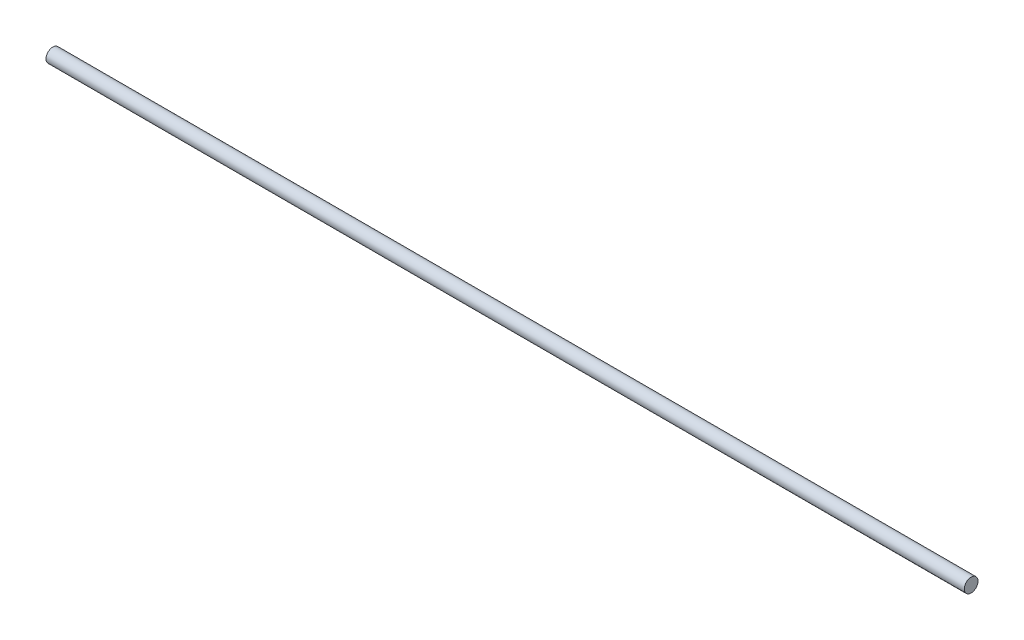
SolidWorks part; units mm, degrees
ref_plane "Front Plane" through (0, 0, 0) normal (0, 0, 1) x (1, 0, 0)
ref_plane "Top Plane" through (0, 0, 0) normal (0, 1, 0) x (1, 0, 0)
ref_plane "Right Plane" through (0, 0, 0) normal (1, 0, 0) x (0, 0, -1)
sketch "Sketch2" plane through (0, 0, 0) normal (0, 0, 1) x (1, 0, 0)
  line L0 (0, 0) -> (0, 1.5)
  line L1 (0, 1.5) -> (-200, 1.5)
  line L2 (-200, 1.5) -> (-200, 0.75)
  line L3 (-190, 0) -> (0, 0)
  line L4 (-190, 0) -> (-190, 0.75)
  line L5 (-190, 0.75) -> (-200, 0.75)
  dimension "D1" = 200
  dimension "D2" = 1.5
  dimension "D3" = 10
  dimension "D4" = 0.75
revolve "Revolve1" add sketch "Sketch2" angle 360 about L3
